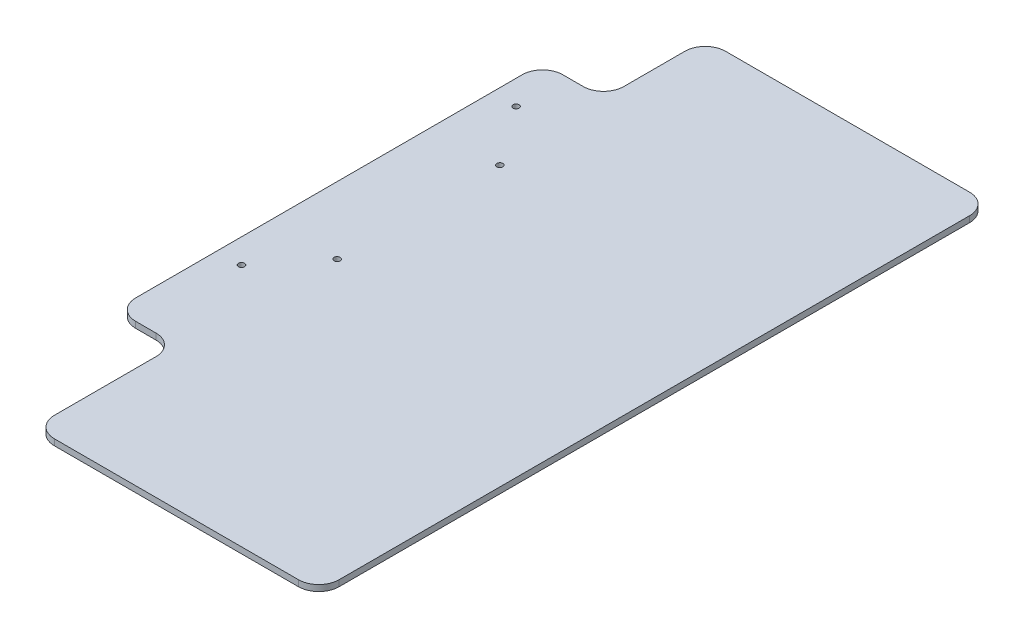
SolidWorks part; units mm, degrees
ref_plane "Front" through (0, 0, 0) normal (0, 0, 1) x (1, 0, 0)
ref_plane "Top" through (0, 0, 0) normal (0, 1, 0) x (1, 0, 0)
ref_plane "Right" through (0, 0, 0) normal (1, 0, 0) x (0, 0, -1)
sketch "草图1" plane through (0, 0, 0) normal (0, 1, 0) x (1, 0, 0)
  line L1 (0, 0) -> (170, 0)
  line L2 (0, 0) -> (0, 220)
  line L3 (0, 220) -> (170, 220)
  line L4 (170, 0) -> (170, 220)
  dimension "D1" = 220
  dimension "D2" = 170
extrude "凸台-拉伸1" add sketch "草图1" along normal blind 3
sketch "草图3" plane through (0, 3, 0) normal (0, 1, 0) x (1, 0, 0)
  circle A1 centre (33, 86) radius 1.5
  circle A3 centre (33, 166) radius 1.5
  dimension "D2" = 3
  dimension "D4" = 3
extrude "切除-拉伸1" cut sketch "草图3" against normal through all
sketch "草图4" plane through (0, 3, 0) normal (0, 1, 0) x (1, 0, 0)
  line L0 (12, 220) -> (12, 0) construction
  line L1 (170, 220) -> (0, 220) construction
  line L2 (0, 0) -> (170, 0) construction
  line L3 (0, 220) -> (0, 0) construction
  circle A0 centre (12, 195) radius 1.5
  circle A1 centre (12, 60) radius 1.5
  dimension "D2" = 3
  dimension "D3" = 3
  dimension "D1" = 12
  dimension "D4" = 25
  dimension "D5" = 135
extrude "切除-拉伸2" cut sketch "草图4" against normal through all
sketch "草图5" plane through (0, 3, 0) normal (0, 1, 0) x (1, 0, 0)
  line L0 (170, 0) -> (170, 220) construction
  line L1 (0, 0) -> (170, 0)
  line L2 (0, 0) -> (0, 10)
  line L3 (0, 10) -> (170, 10)
  line L4 (170, 0) -> (170, 10)
  dimension "D1" = 10
extrude "切除-拉伸3" cut sketch "草图5" against normal through all
sketch "草图6" plane through (0, 3, 0) normal (0, 1, 0) x (1, 0, 0)
  line L0 (40, 195) -> (150, 195) construction
  line L1 (40, 200) -> (150, 200)
  line L2 (40, 190) -> (150, 190)
  line L4 (170, 220) -> (0, 220) construction
  line L5 (0, 220) -> (0, 10) construction
  line L6 (40, 145) -> (150, 145) construction
  line L7 (40, 150) -> (150, 150)
  line L8 (40, 140) -> (150, 140)
  line L9 (40, 95) -> (150, 95) construction
  line L10 (40, 100) -> (150, 100)
  line L11 (40, 90) -> (150, 90)
  line L12 (40, 45) -> (150, 45) construction
  line L13 (40, 50) -> (150, 50)
  line L14 (40, 40) -> (150, 40)
  arc A0 (40, 200) -> (40, 190) centre (40, 195) ccw
  arc A1 (150, 190) -> (150, 200) centre (150, 195) ccw
  arc A2 (40, 150) -> (40, 140) centre (40, 145) ccw
  arc A3 (150, 140) -> (150, 150) centre (150, 145) ccw
  arc A4 (40, 100) -> (40, 90) centre (40, 95) ccw
  arc A5 (150, 90) -> (150, 100) centre (150, 95) ccw
  arc A6 (40, 50) -> (40, 40) centre (40, 45) ccw
  arc A7 (150, 40) -> (150, 50) centre (150, 45) ccw
  point P2 (95, 195)
  point P14 (95, 145)
  point P21 (95, 95)
  point P28 (95, 45)
  dimension "D1" = 5
  dimension "D2" = 20
  dimension "D3" = 40
  dimension "D4" = 110
  dimension "D5" = 4
extrude "切除-拉伸4" [suppressed] cut sketch "草图6" against normal through all
sketch "草图7" plane through (0, 3, 0) normal (0, 1, 0) x (1, 0, 0)
  line L1 (170, 220) -> (30, 220)
  line L2 (170, 220) -> (170, 270)
  line L3 (170, 270) -> (30, 270)
  line L4 (30, 220) -> (30, 270)
  line L5 (170, 10) -> (30, 10)
  line L6 (170, 10) -> (170, -60)
  line L7 (170, -60) -> (30, -60)
  line L8 (30, 10) -> (30, -60)
  dimension "D1" = 70
  dimension "D2" = 50
  dimension "D3" = 140
extrude "凸台-拉伸2" add sketch "草图7" against normal up to surface (3 mm away) up to face at (85, 0, -115)
fillet "圆角1" radius 10 8 edges at (170, 1.5, 60) (30, 1.5, -10) (30, 1.5, 60) (0, 1.5, -10) (0, 1.5, -220) (30, 1.5, -220) (30, 1.5, -270) (170, 1.5, -270)
